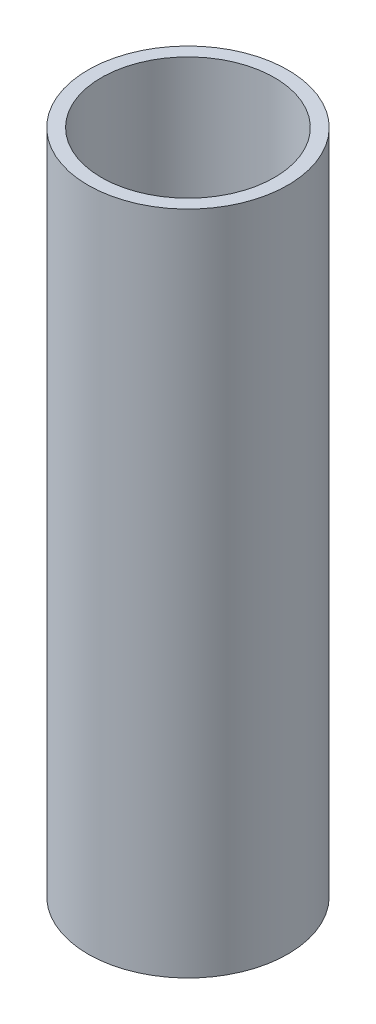
SolidWorks part; units mm, degrees
material "Hexcel AS4C (3000 Filaments)"
ref_plane "Front Plane" through (0, 0, 0) normal (0, 0, 1) x (1, 0, 0)
ref_plane "Top Plane" through (0, 0, 0) normal (0, 1, 0) x (1, 0, 0)
ref_plane "Right Plane" through (0, 0, 0) normal (1, 0, 0) x (0, 0, -1)
sketch "Sketch2" plane through (0, 0, 0) normal (0, 1, 0) x (1, 0, 0)
  circle A0 centre (0, 0) radius 15
  circle A1 centre (0, 0) radius 13
  dimension "D1" = 30
  dimension "D2" = 26
extrude "Boss-Extrude1" add sketch "Sketch2" along normal blind 100
